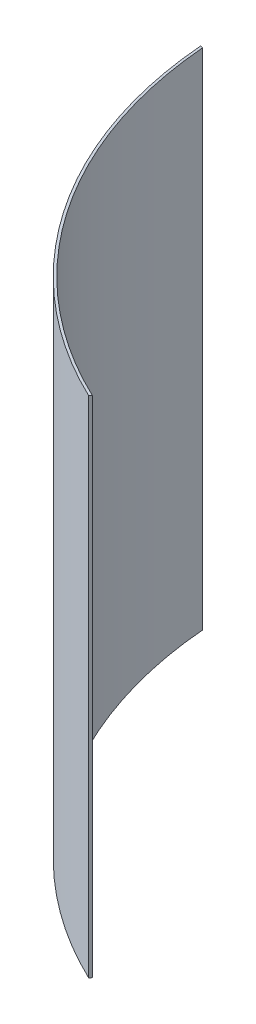
SolidWorks part; units mm, degrees
material "1060 Alloy"
ref_plane "Front Plane" through (0, 0, 0) normal (0, 0, 1) x (1, 0, 0)
ref_plane "Top Plane" through (0, 0, 0) normal (0, 1, 0) x (1, 0, 0)
ref_plane "Right Plane" through (0, 0, 0) normal (1, 0, 0) x (0, 0, -1)
sketch "Sketch1" plane through (0, 0, 0) normal (0, 1, 0) x (1, 0, 0)
  line L0 (-746.1681, -1571.8886) -> (-752.2641, -1580.0629)
  line L1 (-1744.5066, -138.5516) -> (-1734.3547, -140.0516)
  arc A0 (-752.2641, -1580.0629) -> (-1744.5066, -138.5516) centre (0, 0) cw
  arc A1 (-1734.3547, -140.0516) -> (-746.1681, -1571.8886) centre (0, 0) ccw
extrude "Boss-Extrude1" add sketch "Sketch1" along normal blind 2025.87
